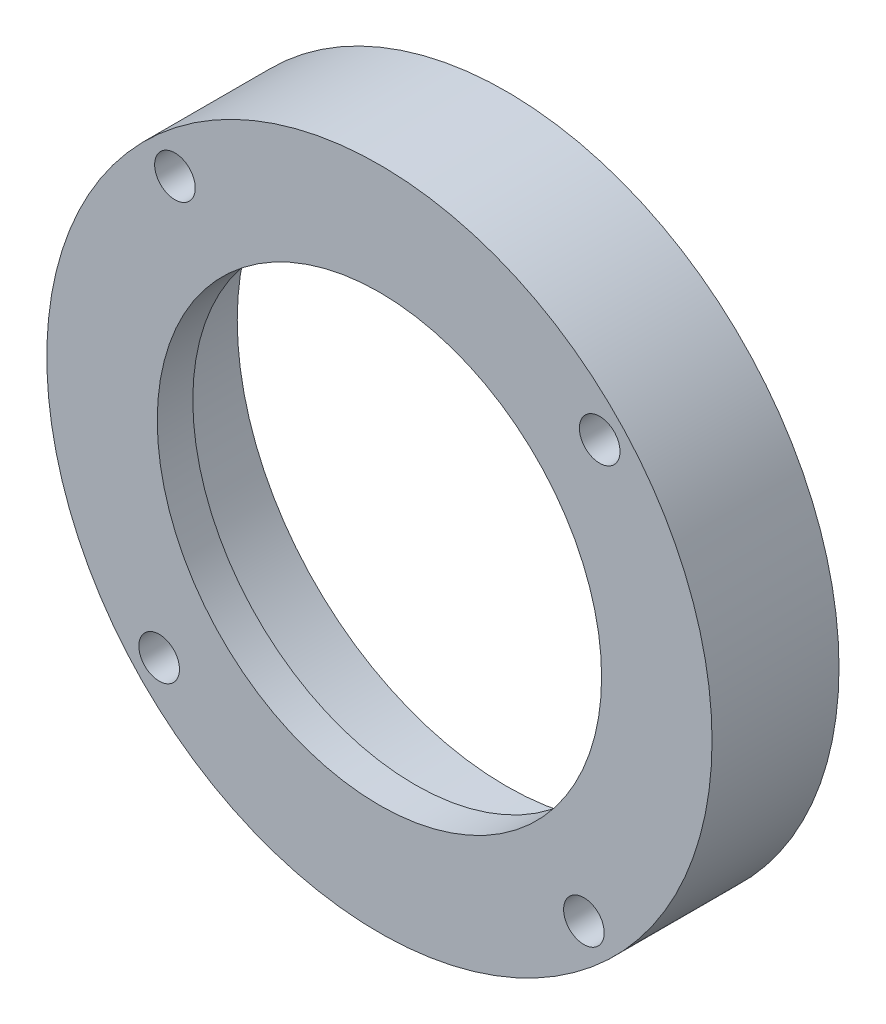
SolidWorks part; units mm, degrees
ref_plane "Front Plane" through (0, 0, 0) normal (0, 0, 1) x (1, 0, 0)
ref_plane "Top Plane" through (0, 0, 0) normal (0, 1, 0) x (1, 0, 0)
ref_plane "Right Plane" through (0, 0, 0) normal (1, 0, 0) x (0, 0, -1)
sketch "Sketch1" plane through (0, 0, 0) normal (0, 0, 1) x (1, 0, 0)
  circle A1 centre (0, 0) radius 26.2
  circle A2 centre (17.3492, 16.1057) radius 1.6 construction
  circle A3 centre (16.1057, -17.3492) radius 1.6 construction
  circle A4 centre (-16.1057, 17.3492) radius 1.6 construction
  circle A5 centre (-17.3492, -16.1057) radius 1.6 construction
  circle A6 centre (17.3492, 16.1057) radius 1.6
  circle A7 centre (16.1057, -17.3492) radius 1.6
  circle A8 centre (-16.1057, 17.3492) radius 1.6
  circle A9 centre (-17.3492, -16.1057) radius 1.6
  circle A10 centre (0, 0) radius 17.5
extrude "Boss-Extrude1" add sketch "Sketch1" along normal blind 10
sketch "Sketch2" plane through (0, 0, 0) normal (0, 0, -1) x (-1, 0, 0)
  circle A0 centre (0, 0) radius 21.2
extrude "Cut-Extrude1" cut sketch "Sketch2" against normal blind 7.2
